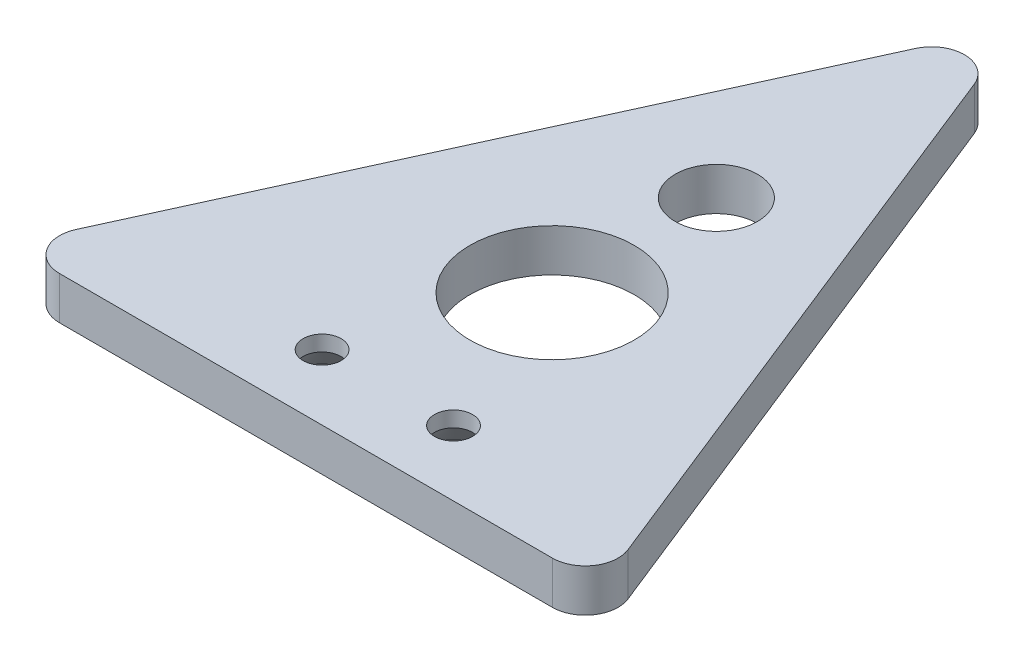
SolidWorks part; units mm, degrees
material "Free-Cutting Brass, UNS C36000"
ref_plane "Front Plane" through (0, 0, 0) normal (0, 0, 1) x (1, 0, 0)
ref_plane "Top Plane" through (0, 0, 0) normal (0, 1, 0) x (1, 0, 0)
ref_plane "Right Plane" through (0, 0, 0) normal (1, 0, 0) x (0, 0, -1)
other "Center of Mass"
sketch "Sketch1" plane through (0, 0, 0) normal (0, 1, 0) x (1, 0, 0)
  line L0 (0, 0) -> (10.16, 0) construction
  line L26 (5.08, 0) -> (5.08, 42.037) construction
  line L27 (0, 0) -> (0, 10.16) construction
  line L28 (7.4391, 42.9785) -> (25.2191, -1.5731)
  line L29 (22.86, -5.0546) -> (-15.24, -5.0546)
  line L30 (-17.551, -1.4606) -> (2.769, 43.091)
  circle A2 centre (0, 0) radius 1.1303
  circle A3 centre (10.16, 0) radius 1.1303
  arc A5 (-15.24, -5.0546) -> (-17.551, -1.4606) centre (-15.24, -2.5146) cw
  arc A6 (25.2191, -1.5731) -> (22.86, -5.0546) centre (22.86, -2.5146) cw
  arc A7 (7.4391, 42.9785) -> (2.769, 43.091) centre (5.08, 42.037) ccw
  dimension "D3" = 2.54
  dimension "D5" = 2.2606
  dimension "D6" = 2.2606
  dimension "D1" = 10.16
  dimension "D7" = 2.54
  dimension "D2" = 20.32
  dimension "D9" = 2.54
  dimension "D4" = 42.037
  dimension "D8" = 10.16
  dimension "D10" = 12.7
  dimension "D11" = 47.0916
extrude "Boss-Extrude1" add sketch "Sketch1" along normal blind 3.302
hole_wizard "#4 Clearance Hole1" positions "Sketch15" profile "Sketch16" hole size "#4" standard "ANSI Inch" end condition through all
sketch "Sketch15" plane through (0, 0, 0) normal (0, -1, 0) x (-1, 0, 0)
  point P0 (0, 0)
  point P3 (-10.16, 0)
sketch "Sketch16" plane through (0, 0, 0) normal (1, 0, 0) x (0, 0, -1)
  line L0 (0, 0) -> (0, 3.302)
  line L1 (0, 3.302) -> (1.4732, 3.302)
  line L2 (1.4732, 3.302) -> (1.4732, 2.1038)
  line L3 (1.4732, 2.1038) -> (3.302, 0)
  line L5 (3.302, 0) -> (0, 0)
  line L6 (-1.4732, 2.1038) -> (-3.302, 0) construction
  line L11 (0, -6.35) -> (0, 107.95) construction
  dimension "Thru Hole Dia." = 2.9464
  dimension "Thru Hole Depth" = 3.302
  dimension "Near C'Sink Dia." = 6.604
  dimension "Near C'Sink Angle" = 82
sketch "Sketch17" plane through (0, 0, 0) normal (0, -1, 0) x (1, 0, 0)
  line L0 (5.08, 0) -> (5.08, -12.7) construction
  line L1 (0, 0) -> (10.16, 0) construction
  circle A0 centre (5.08, -12.7) radius 6.35
  dimension "D1" = 12.7
  dimension "D2" = 12.7
extrude "Cut-Extrude1" cut sketch "Sketch17" against normal through all
sketch "Sketch18" plane through (0, 0, 0) normal (0, -1, 0) x (1, 0, 0)
  line L0 (5.08, -12.7) -> (5.08, -25.4) construction
  circle A0 centre (5.08, -25.4) radius 3.175
  circle A1 centre (5.08, -12.7) radius 6.35 construction
  dimension "D2" = 6.35
  dimension "D1" = 12.7
extrude "Cut-Extrude2" cut sketch "Sketch18" against normal through all
sketch "Sketch19" plane through (0, 0, 0) normal (0, -1, 0) x (-1, 0, 0)
  line L0 (-25.2191, -1.5731) -> (-28.985, -11.0094)
  line L1 (-25.2191, -1.5731) -> (-2.6236, 55.0446)
  line L2 (-7.4391, 42.9785) -> (-25.2191, -1.5731) construction
  dimension "D1" = 10.16
  dimension "D2" = 60.96
